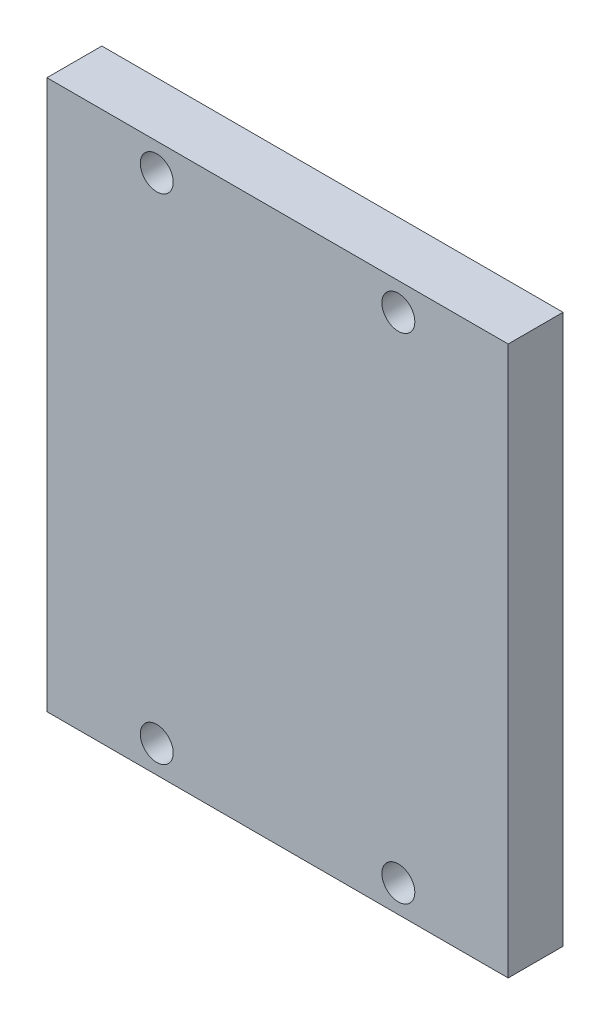
SolidWorks part; units mm, degrees
ref_plane "Front Plane" through (0, 0, 0) normal (0, 0, 1) x (1, 0, 0)
ref_plane "Top Plane" through (0, 0, 0) normal (0, 1, 0) x (1, 0, 0)
ref_plane "Right Plane" through (0, 0, 0) normal (1, 0, 0) x (0, 0, -1)
sketch "Sketch1" plane through (0, 0, 0) normal (0, 0, 1) x (1, 0, 0)
  line L1 (0, 0) -> (42, 0)
  line L2 (0, 0) -> (0, 25)
  line L3 (0, 25) -> (42, 25)
  line L4 (42, 0) -> (42, 25)
  circle A0 centre (10, 2.5) radius 1.5
  circle A1 centre (32, 2.5) radius 1.5
  dimension "D6" = 3
  dimension "D8" = 3
  dimension "D1" = 25
  dimension "D2" = 42
  dimension "D3" = 10
  dimension "D4" = 10
  dimension "D5" = 2.5
  dimension "D7" = 2.5
extrude "Boss-Extrude1" add sketch "Sketch1" along normal blind 5
mirror "Mirror1" about plane through (0, 25, 5) normal (0, -1, 0) of "Boss-Extrude1"
